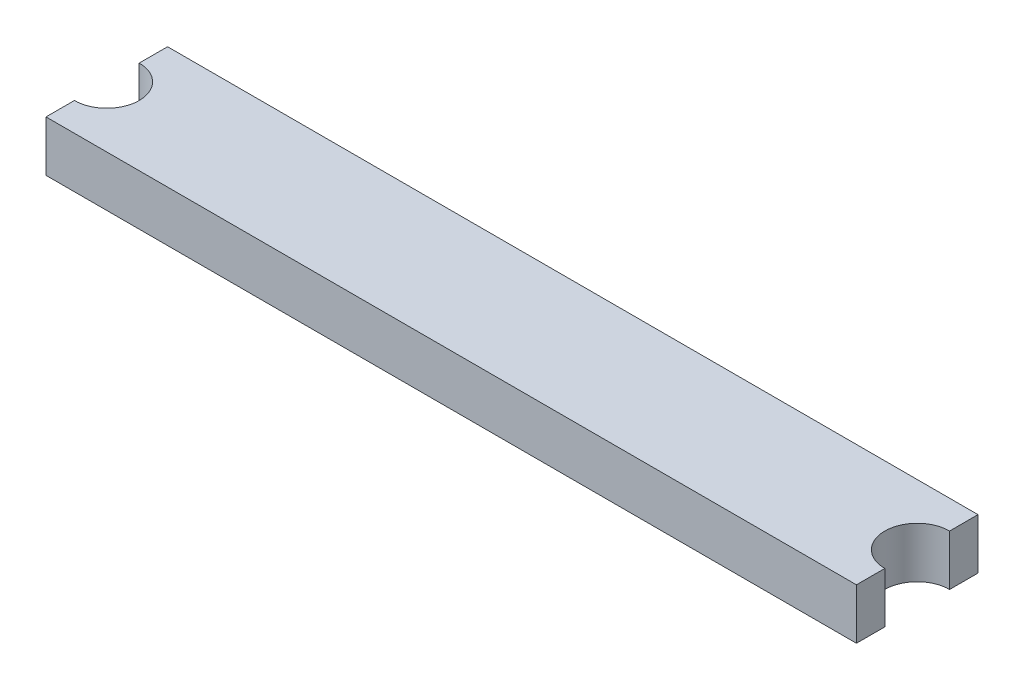
SolidWorks part; units mm, degrees
ref_plane "Front Plane" through (0, 0, 0) normal (0, 0, 1) x (1, 0, 0)
ref_plane "Top Plane" through (0, 0, 0) normal (0, 1, 0) x (1, 0, 0)
ref_plane "Right Plane" through (0, 0, 0) normal (1, 0, 0) x (0, 0, -1)
sketch "Sketch2" plane through (0, 0, 0) normal (0, 1, 0) x (1, 0, 0)
  line L1 (-200, 30) -> (200, 30)
  line L2 (-200, 30) -> (-200, -30)
  line L3 (-200, -30) -> (200, -30)
  line L4 (200, 30) -> (200, -30)
  line L5 (-200, 30) -> (200, -30) construction
  line L6 (-200, -30) -> (200, 30) construction
  point P0 (0, 0)
  dimension "D1" = 400
  dimension "D2" = 60
extrude "Boss-Extrude1" add sketch "Sketch2" along normal blind 25
sketch "Sketch3" plane through (0, 25, 0) normal (0, 1, 0) x (1, 0, 0)
  line L0 (200, -30) -> (200, 30) construction
  circle A0 centre (-200, 0) radius 16
  circle A1 centre (200, 0) radius 16
  point P6 (0, 0)
  dimension "D1" = 32
  dimension "D2" = 32
extrude "Cut-Extrude2" cut sketch "Sketch3" against normal through all contours A0 | A1
